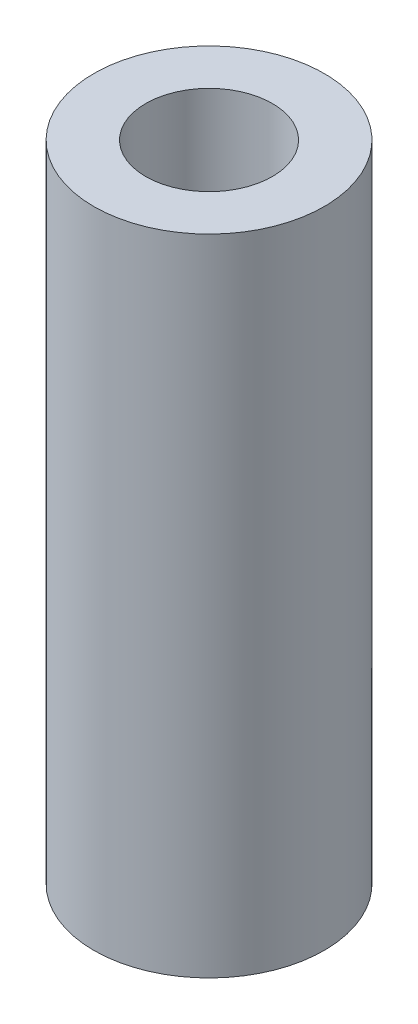
SolidWorks part; units mm, degrees
ref_plane "Front Plane" through (0, 0, 0) normal (0, 0, 1) x (1, 0, 0)
ref_plane "Top Plane" through (0, 0, 0) normal (0, 1, 0) x (1, 0, 0)
ref_plane "Right Plane" through (0, 0, 0) normal (1, 0, 0) x (0, 0, -1)
sketch "Sketch1" plane through (0, 0, 0) normal (0, 1, 0) x (1, 0, 0)
  circle A0 centre (0, 0) radius 2.1844
  circle A1 centre (0, 0) radius 3.9751
  dimension "D1" = 4.3688
  dimension "D2" = 7.9502
extrude "Boss-Extrude1" add sketch "Sketch1" along normal blind 22.225
